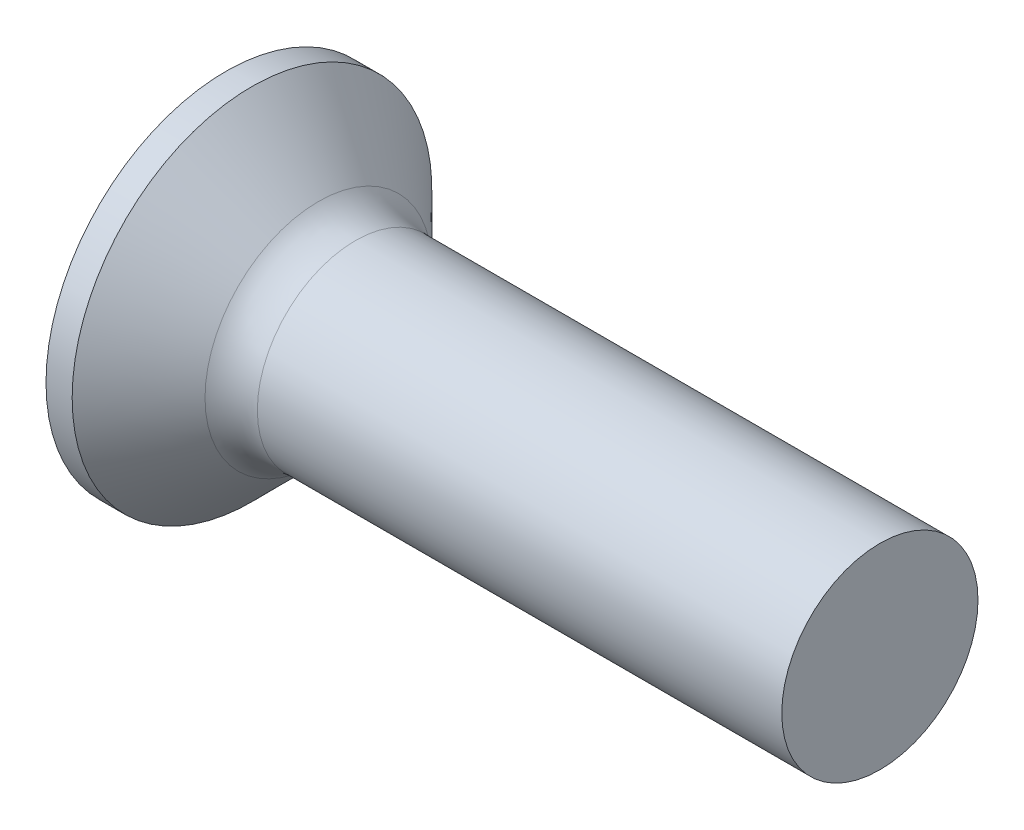
SolidWorks part; units mm, degrees
revolve "Base-Revolve" add sketch "BodySke" angle 360 about L5
sketch "BodySke" plane through (0, 0, 0) normal (0, 0, 1) x (1, 0, 0)
  line L0 (0, 0) -> (0, 2.75)
  line L1 (0, 2.75) -> (0.4, 2.75)
  line L2 (1.65, 1.5) -> (10, 1.5)
  line L3 (10, 1.5) -> (10, 0)
  line L4 (10, 0) -> (0, 0)
  line L5 (-6.35, 0) -> (82.55, 0) construction
  line L6 (1.65, -1.5) -> (10, -1.5) construction
  line L7 (0.4, -2.75) -> (1.65, -1.5) construction
  line L8 (0.4, 2.75) -> (1.65, 1.5)
  line L9 (0, -2.75) -> (0.4, -2.75) construction
  line L10 (2.15, 3.0875) -> (2.15, -6.4375) construction
  line L11 (0, 6.35) -> (0, -3.175) construction
  dimension "Diameter" = 3
  dimension "Length" = 10
  dimension "Head_ht" = 1.65
  dimension "Head_dia" = 5.5
  dimension "Head_ang" = 90
  dimension "D6" = 0.4
  dimension "Advance" = 0.5
  dimension "Thread_nom" = 10
cosmetic thread "ThreadCosmetic" [suppressed] parameters "Thread_length"=7.85, "Thread_minor"=2.439
ref_plane "Plane1" through (0, 0, 0) normal (0, 0, 1) x (1, 0, 0)
ref_plane "Plane2" through (0, 0, 0) normal (0, 1, 0) x (1, 0, 0)
ref_plane "Plane3" through (0, 0, 0) normal (1, 0, 0) x (0, 0, -1)
other "Configuration Table"
fillet "Fillet1" radius 0.8 1 edges at (1.65, 0, 1.5)
sketch "Sketch3" plane through (0, 0, 0) normal (-1, 0, 0) x (0, 0, 1)
  line L0 (-0.37, 1.5) -> (0.37, 1.5)
  line L1 (0.37, 1.5) -> (0.37, -1.5)
  line L2 (0.37, -1.5) -> (-0.37, -1.5)
  line L3 (-0.37, -1.5) -> (-0.37, 1.5)
  dimension "Cross_dia" = 3
  dimension "Cross_width" = 0.74
  dimension "D1" = 1.5
  dimension "D2" = 0.37
ref_plane "Plane4" through (2.01, 0, 0) normal (-1, 0, 0) x (0, 0, 1)
sketch "Sketch4" plane through (2.01, 0, 0) normal (-1, 0, 0) x (0, 0, 1)
  line L0 (-0.37, 0.4979) -> (0.37, 0.4979)
  line L3 (0.37, 0.4979) -> (0.37, -0.4979)
  line L4 (0.37, -0.4979) -> (-0.37, -0.4979)
  line L5 (-0.37, -0.4979) -> (-0.37, 0.4979)
  dimension "D2" = 0.9957
  dimension "D1" = 0.74
  dimension "D4" = 0.4979
  dimension "D3" = 0.37
loft "Recess" cut profiles "Sketch3", "Sketch4"
pattern_circular "RecPat" count 2 every 90 about axis through (0, 0, 0) along (1, 0, 0) of "Recess"
sketch "RecCorSke" plane through (0, 0, 0) normal (0, 0, 1) x (1, 0, 0)
  line L0 (-3.175, 0) -> (15.875, 0) construction
  line L2 (0, 0) -> (0, 0.6966)
  line L3 (0, 0.6966) -> (2.01, 0.556)
  line L4 (2.01, 0.556) -> (2.1907, 0)
  line L5 (2.1907, 0) -> (0, 0)
  dimension "Diameter" = 1.112
  dimension "Depth" = 2.01
  dimension "Draft_angle" = 4
  dimension "Bottom_angle" = 18
revolve "RecessCore" cut sketch "RecCorSke" angle 360 about L0
sketch "ThdSchSke" plane through (0, 0, 0) normal (0, 0, 1) x (1, 0, 0)
  line L0 (2.15, -1.2195) -> (1.9536, -1.5)
  line L1 (2.15, -1.2195) -> (2.3464, -1.5)
  line L2 (2.3464, -1.5) -> (2.3464, -1.875)
  line L3 (-3.175, 0) -> (5.1513, 0) construction
  line L5 (2.3464, -1.875) -> (1.9536, -1.875)
  line L6 (1.9536, -1.875) -> (1.9536, -1.5)
  line L7 (0, 2.75) -> (0, -2.75) construction
  dimension "Diameter" = 3
  dimension "Thread_minor" = 2.439
  dimension "Start" = 2.15
revolve "ThreadSchematic" [suppressed] cut sketch "ThdSchSke" angle 360 about L3
pattern_linear "ThdSchPat" [suppressed]
equation "\"D1@Sketch3\" = \"Cross_dia@Sketch3\" / 2"
equation "\"D2@Sketch3\" = \"Cross_width@Sketch3\" / 2"
equation "\"Depth@RecCorSke\" = \"Cross_depth@Plane4\""
equation "\"D1@Sketch4\" = \"Cross_width@Sketch3\""
equation "\"D2@Sketch4\" = \"Cross_dia@Sketch3\" - 2.0 * \"Cross_depth@Plane4\" * tan(26.5  * 0.017453292)"
equation "\"D3@Sketch4\" = \"D1@Sketch4\" / 2"
equation "\"D4@Sketch4\" = \"D2@Sketch4\" / 2"
equation "\"Thread_length@ThreadCosmetic\" = ((sgn( (\"Length@BodySke\" - \"Advance@BodySke\" * 1.0 - \"Head_ht@BodySke\" ) - \"Thread_nom@BodySke\" )-1)*( (\"Length@BodySke\" - \"Advance@BodySke\" * 1.0 - \"Head_ht@BodySke\" ) - \"Thread_nom@BodySke\" ))/-2+ \"Thread_nom@BodySke\""
equation "\"Thread_minor@ThdSchSke\" = \"Thread_minor@ThreadCosmetic\""
equation "\"Diameter@ThdSchSke\" = \"Diameter@BodySke\""
equation "\"Overcut@ThdSchSke\" = \"Diameter@BodySke\" * 1.25"
equation "\"Start@ThdSchSke\" = 0.000001 + \"Length@BodySke\" - \"Thread_length@ThreadCosmetic\"  '---Countersunk---"
equation "\"Num_threads@ThdSchPat\" = int( \"Thread_length@ThreadCosmetic\" / \"Advance@BodySke\" + 0.999 )  + 1"
equation "\"Advance@ThdSchPat\" = \"Thread_length@ThreadCosmetic\" /  (\"Num_threads@ThdSchPat\" - 1) 'relax it"
